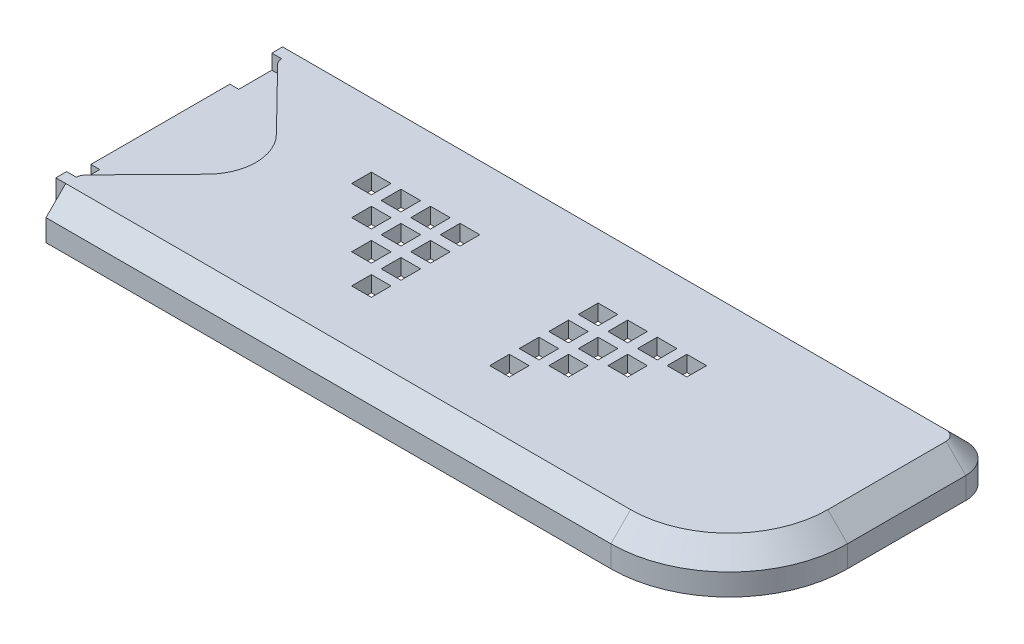
SolidWorks part; units mm, degrees
ref_plane "Спереди" through (0, 0, 0) normal (0, 0, 1) x (1, 0, 0)
ref_plane "Сверху" through (0, 0, 0) normal (0, 1, 0) x (1, 0, 0)
ref_plane "Справа" through (0, 0, 0) normal (1, 0, 0) x (0, 0, -1)
sketch "Эскиз1" plane through (0, 1.5, 0) normal (0, 1, 0) x (1, 0, 0)
  line L1 (46.05, -0.9) -> (-4.2, -0.9) construction
  line L2 (-4.2, -0.9) -> (-4.2, 1.1) construction
  line L3 (-4.2, 1.1) -> (-5.2, 1.1) construction
  line L4 (-5.2, 1.1) -> (-5.2, 4.95) construction
  line L5 (-5.2, 4.95) -> (-7.7, 4.95) construction
  line L6 (-7.7, 4.95) -> (-7.7, 3.95) construction
  line L7 (-7.7, 3.95) -> (-6.8, 3.95) construction
  line L8 (-6.8, 3.95) -> (-6.8, -0.5) construction
  line L9 (-6.8, -0.5) -> (-5.8, -0.5) construction
  line L10 (-5.8, -0.5) -> (-5.8, -2.5) construction
  line L11 (-5.8, -2.5) -> (46.05, -2.5) construction
  line L13 (50.55, -2.5) -> (51.5, -2.5) construction
  line L14 (63.5, 9.5) -> (63.5, 21.5) construction
  line L15 (60.5, 24.5) -> (-5.8, 24.5) construction
  line L16 (-5.8, 24.5) -> (-5.8, 22.5) construction
  line L17 (-5.8, 22.5) -> (-6.8, 22.5) construction
  line L18 (-6.8, 22.5) -> (-6.8, 18.05) construction
  line L19 (-6.8, 18.05) -> (-7.7, 18.05) construction
  line L20 (-7.7, 18.05) -> (-7.7, 17.05) construction
  line L21 (-7.7, 17.05) -> (-5.2, 17.05) construction
  line L22 (-5.2, 17.05) -> (-5.2, 20.9) construction
  line L23 (-5.2, 20.9) -> (-4.2, 20.9) construction
  line L24 (-4.2, 20.9) -> (-4.2, 22.9) construction
  line L25 (-4.2, 22.9) -> (60.5, 22.9) construction
  line L26 (61.9, 21.5) -> (61.9, 9.5) construction
  line L27 (51.5, -0.9) -> (50.55, -0.9) construction
  line L29 (46.05, -0.9) -> (-4.2, -0.9)
  line L30 (-4.2, -0.9) -> (-4.2, 1.1)
  line L31 (-4.2, 1.1) -> (-5.2, 1.1)
  line L32 (-5.2, 1.1) -> (-5.2, 4.95)
  line L33 (-5.2, 4.95) -> (-7.7, 4.95)
  line L34 (-7.7, 4.95) -> (-7.7, 3.95)
  line L35 (-7.7, 3.95) -> (-6.8, 3.95)
  line L36 (-6.8, 3.95) -> (-6.8, -0.5)
  line L37 (-6.8, -0.5) -> (-5.8, -0.5)
  line L38 (-5.8, -0.5) -> (-5.8, -2.5)
  line L39 (-5.8, -2.5) -> (46.05, -2.5)
  line L41 (50.55, -2.5) -> (51.5, -2.5)
  line L42 (63.5, 9.5) -> (63.5, 21.5)
  line L43 (60.5, 24.5) -> (-5.8, 24.5)
  line L44 (-5.8, 24.5) -> (-5.8, 22.5)
  line L45 (-5.8, 22.5) -> (-6.8, 22.5)
  line L46 (-6.8, 22.5) -> (-6.8, 18.05)
  line L47 (-6.8, 18.05) -> (-7.7, 18.05)
  line L48 (-7.7, 18.05) -> (-7.7, 17.05)
  line L49 (-7.7, 17.05) -> (-5.2, 17.05)
  line L50 (-5.2, 17.05) -> (-5.2, 20.9)
  line L51 (-5.2, 20.9) -> (-4.2, 20.9)
  line L52 (-4.2, 20.9) -> (-4.2, 22.9)
  line L53 (-4.2, 22.9) -> (60.5, 22.9)
  line L54 (61.9, 21.5) -> (61.9, 9.5)
  line L55 (51.5, -0.9) -> (50.55, -0.9)
  line L56 (50.55, -0.9) -> (46.05, -0.9)
  line L57 (50.55, -2.5) -> (46.05, -2.5)
  arc A0 (51.5, -2.5) -> (63.5, 9.5) centre (51.5, 9.5) ccw construction
  arc A1 (63.5, 21.5) -> (60.5, 24.5) centre (60.5, 21.5) ccw construction
  arc A2 (61.9, 21.5) -> (60.5, 22.9) centre (60.5, 21.5) ccw construction
  arc A3 (51.5, -0.9) -> (61.9, 9.5) centre (51.5, 9.5) ccw construction
  arc A4 (51.5, -2.5) -> (63.5, 9.5) centre (51.5, 9.5) ccw
  arc A5 (63.5, 21.5) -> (60.5, 24.5) centre (60.5, 21.5) ccw
  arc A6 (61.9, 21.5) -> (60.5, 22.9) centre (60.5, 21.5) ccw
  arc A7 (51.5, -0.9) -> (61.9, 9.5) centre (51.5, 9.5) ccw
extrude "Бобышка-Вытянуть1" add sketch "Эскиз1" along normal blind 4.2
sketch "Эскиз2" plane through (0, 5.7, 0) normal (0, 1, 0) x (1, 0, 0)
  line L0 (-7.7, 17.05) -> (-7.7, 4.95)
  line L24 (-5.8, -2.5) -> (51.5, -2.5)
  line L25 (63.5, 9.5) -> (63.5, 21.5)
  line L26 (60.5, 24.5) -> (-5.8, 24.5)
  line L27 (-5.8, 24.5) -> (-5.8, 22.5)
  line L28 (-5.8, 22.5) -> (-6.8, 22.5)
  line L29 (-6.8, 22.5) -> (-6.8, 18.05)
  line L30 (-6.8, 18.05) -> (-7.7, 18.05)
  line L31 (-7.7, 18.05) -> (-7.7, 17.05)
  line L32 (-7.7, 17.05) -> (-5.2, 17.05)
  line L33 (-5.2, 17.05) -> (-5.2, 20.9)
  line L34 (-5.2, 20.9) -> (-4.2, 20.9)
  line L35 (-4.2, 20.9) -> (-4.2, 22.9)
  line L36 (-4.2, 22.9) -> (60.5, 22.9)
  line L37 (61.9, 21.5) -> (61.9, 9.5)
  line L38 (51.5, -0.9) -> (-4.2, -0.9)
  line L39 (-4.2, -0.9) -> (-4.2, 1.1)
  line L40 (-4.2, 1.1) -> (-5.2, 1.1)
  line L41 (-5.2, 1.1) -> (-5.2, 4.95)
  line L42 (-5.2, 4.95) -> (-7.7, 4.95)
  line L43 (-7.7, 4.95) -> (-7.7, 3.95)
  line L44 (-7.7, 3.95) -> (-6.8, 3.95)
  line L45 (-6.8, 3.95) -> (-6.8, -0.5)
  line L46 (-6.8, -0.5) -> (-5.8, -0.5)
  line L47 (-5.8, -0.5) -> (-5.8, -2.5)
  line L48 (-5.8, -2.5) -> (51.5, -2.5)
  line L49 (63.5, 9.5) -> (63.5, 21.5)
  line L50 (60.5, 24.5) -> (-5.8, 24.5)
  line L51 (-5.8, 24.5) -> (-5.8, 22.5)
  line L52 (-5.8, 22.5) -> (-6.8, 22.5)
  line L53 (-6.8, 22.5) -> (-6.8, 18.05)
  line L54 (-6.8, 18.05) -> (-7.7, 18.05)
  line L55 (-7.7, 18.05) -> (-7.7, 17.05)
  line L67 (-7.7, 4.95) -> (-7.7, 3.95)
  line L68 (-7.7, 3.95) -> (-6.8, 3.95)
  line L69 (-6.8, 3.95) -> (-6.8, -0.5)
  line L70 (-6.8, -0.5) -> (-5.8, -0.5)
  line L71 (-5.8, -0.5) -> (-5.8, -2.5)
  arc A4 (51.5, -2.5) -> (63.5, 9.5) centre (51.5, 9.5) ccw
  arc A5 (63.5, 21.5) -> (60.5, 24.5) centre (60.5, 21.5) ccw
  arc A6 (61.9, 21.5) -> (60.5, 22.9) centre (60.5, 21.5) ccw
  arc A7 (51.5, -0.9) -> (61.9, 9.5) centre (51.5, 9.5) ccw
  arc A8 (51.5, -2.5) -> (63.5, 9.5) centre (51.5, 9.5) ccw
  arc A9 (63.5, 21.5) -> (60.5, 24.5) centre (60.5, 21.5) ccw
  dimension "D1" = 0
extrude "Бобышка-Вытянуть2" add sketch "Эскиз2" against normal blind 1.6
chamfer "Фаска1" distance 2 angle 45 5 edges at (27.35, 5.7, -24.5) (62.6213, 5.7, -23.6213) (63.5, 5.7, -15.5) (59.9853, 5.7, -1.0147) (22.85, 5.7, 2.5)
sketch "Эскиз3" plane through (0, 5.7, 0) normal (0, 1, 0) x (1, 0, 0)
  line L0 (0.5708, 7.5) -> (-5.5142, 1.2916) construction
  line L1 (-5.5142, 20.7084) -> (0.5708, 14.5) construction
  line L2 (0.5708, 7.5) -> (-5.5142, 1.2916)
  line L3 (-5.5142, 20.7084) -> (0.5708, 14.5)
  line L4 (-5.8, 21.4083) -> (-11.5257, 21.4083)
  line L5 (-11.5257, 21.4083) -> (-11.5257, 0.5917)
  line L6 (-11.5257, 0.5917) -> (-5.8, 0.5917)
  arc A0 (-5.5142, 1.2916) -> (-5.8, 0.5917) centre (-4.8, 0.5917) ccw construction
  arc A1 (-5.8, 21.4083) -> (-5.5142, 20.7084) centre (-4.8, 21.4083) ccw construction
  arc A2 (0.5708, 7.5) -> (0.5708, 14.5) centre (-3.0002, 11) ccw construction
  arc A3 (-5.5142, 1.2916) -> (-5.8, 0.5917) centre (-4.8, 0.5917) ccw
  arc A4 (-5.8, 21.4083) -> (-5.5142, 20.7084) centre (-4.8, 21.4083) ccw
  arc A5 (0.5708, 7.5) -> (0.5708, 14.5) centre (-3.0002, 11) ccw
extrude "Вырез-Вытянуть1" cut sketch "Эскиз3" against normal blind 1.5
sketch "Эскиз4" plane through (0, 4.1, 0) normal (0, -1, 0) x (1, 0, 0)
  line L0 (-4.2, 0.9) -> (2.2241, -8.0938)
  line L1 (-4.2, 0.9) -> (-4.2, -1.1) construction
  line L2 (2.2241, -13.9062) -> (-4.2, -22.9)
  line L3 (-4.2, -20.9) -> (-4.2, -22.9) construction
  line L4 (4.3, -11) -> (-7.7, -11) construction
  line L5 (-7.7, -17.05) -> (-7.7, -4.95) construction
  line L6 (-4.2, 0.9) -> (-5.2, -1.1)
  line L7 (-5.2, -1.1) -> (-5.2, -4.95) construction
  line L8 (-4.2, -1.1) -> (-5.2, -1.1) construction
  line L9 (-5.2, -1.1) -> (-5.998, -4.95)
  line L10 (-5.2, -4.95) -> (-7.7, -4.95) construction
  line L11 (-5.998, -4.95) -> (-7.7, -4.95)
  line L12 (-7.7, -4.95) -> (-7.7, -17.05)
  line L13 (-7.7, -17.05) -> (-5.2, -17.05)
  line L14 (-5.2, -17.05) -> (-5.2, -22.9)
  line L15 (-5.2, -22.9) -> (-4.2, -22.9)
  arc A0 (2.2241, -13.9062) -> (2.2241, -8.0938) centre (-1.8445, -11) ccw
  dimension "D2" = 5
  dimension "D1" = 12
extrude "Бобышка-Вытянуть3" add sketch "Эскиз4" along normal blind 1.5
sketch "Эскиз5" plane through (0, 2.6, 0) normal (0, -1, 0) x (1, 0, 0)
  line L1 (-7.7, -4.95) -> (-5.2, -4.95)
  line L2 (-7.7, -4.95) -> (-7.7, -17.05)
  line L3 (-7.7, -17.05) -> (-5.2, -17.05)
  line L4 (-5.2, -4.95) -> (-5.2, -17.05)
extrude "Бобышка-Вытянуть4" add sketch "Эскиз5" along normal up to surface (1.1 mm away) up to face at (12.9125, 1.5, -11.5097)
sketch "Эскиз6" plane through (0, 5.7, 0) normal (0, 1, 0) x (1, 0, 0)
  line L0 (25.7, 22.5) -> (25.7, -0.5) construction
  line L1 (19.7, 16) -> (17.7, 16)
  line L2 (19.7, 16) -> (19.7, 14)
  line L3 (19.7, 14) -> (17.7, 14)
  line L4 (17.7, 16) -> (17.7, 14)
  line L5 (19.7, 16) -> (17.7, 14) construction
  line L6 (19.7, 14) -> (17.7, 16) construction
  line L7 (60.5, 22.5) -> (-5.8, 22.5) construction
  line L8 (-5.8, -0.5) -> (51.5, -0.5) construction
  line L9 (-5.8, 24.5) -> (60.5, 24.5) construction
  line L10 (-6.8, 21.4083) -> (-6.8, 18.05) construction
  line L11 (16.7, 16) -> (14.7, 16)
  line L12 (16.7, 16) -> (16.7, 14)
  line L13 (16.7, 14) -> (14.7, 14)
  line L14 (14.7, 16) -> (14.7, 14)
  line L15 (13.7, 16) -> (11.7, 16)
  line L16 (13.7, 16) -> (13.7, 14)
  line L17 (13.7, 14) -> (11.7, 14)
  line L18 (11.7, 16) -> (11.7, 14)
  line L19 (10.7, 16) -> (8.7, 16)
  line L20 (10.7, 16) -> (10.7, 14)
  line L21 (10.7, 14) -> (8.7, 14)
  line L22 (8.7, 16) -> (8.7, 14)
  line L23 (19.7, 13) -> (17.7, 13)
  line L24 (19.7, 13) -> (19.7, 11)
  line L25 (19.7, 11) -> (17.7, 11)
  line L26 (17.7, 13) -> (17.7, 11)
  line L27 (16.7, 13) -> (14.7, 13)
  line L28 (16.7, 13) -> (16.7, 11)
  line L29 (16.7, 11) -> (14.7, 11)
  line L30 (14.7, 13) -> (14.7, 11)
  line L31 (13.7, 13) -> (11.7, 13)
  line L32 (13.7, 13) -> (13.7, 11)
  line L33 (13.7, 11) -> (11.7, 11)
  line L34 (11.7, 13) -> (11.7, 11)
  line L39 (19.7, 10) -> (17.7, 10)
  line L40 (19.7, 10) -> (19.7, 8)
  line L41 (19.7, 8) -> (17.7, 8)
  line L42 (17.7, 10) -> (17.7, 8)
  line L43 (16.7, 10) -> (14.7, 10)
  line L44 (16.7, 10) -> (16.7, 8)
  line L45 (16.7, 8) -> (14.7, 8)
  line L46 (14.7, 10) -> (14.7, 8)
  line L55 (19.7, 7) -> (17.7, 7)
  line L56 (19.7, 7) -> (19.7, 5)
  line L57 (19.7, 5) -> (17.7, 5)
  line L58 (17.7, 7) -> (17.7, 5)
  line L71 (16.7, 7) -> (14.7, 7) [skipped]
  line L72 (16.7, 7) -> (16.7, 5) [skipped]
  line L73 (16.7, 5) -> (14.7, 5) [skipped]
  line L74 (14.7, 7) -> (14.7, 5) [skipped]
  line L75 (13.7, 7) -> (11.7, 7) [skipped]
  line L76 (13.7, 7) -> (13.7, 5) [skipped]
  line L77 (13.7, 5) -> (11.7, 5) [skipped]
  line L78 (11.7, 7) -> (11.7, 5) [skipped]
  line L79 (10.7, 7) -> (8.7, 7) [skipped]
  line L80 (10.7, 7) -> (10.7, 5) [skipped]
  line L81 (10.7, 5) -> (8.7, 5) [skipped]
  line L82 (8.7, 7) -> (8.7, 5) [skipped]
  line L83 (13.7, 10) -> (11.7, 10) [skipped]
  line L84 (13.7, 10) -> (13.7, 8) [skipped]
  line L85 (13.7, 8) -> (11.7, 8) [skipped]
  line L86 (11.7, 10) -> (11.7, 8) [skipped]
  line L87 (10.7, 10) -> (8.7, 10) [skipped]
  line L88 (10.7, 10) -> (10.7, 8) [skipped]
  line L89 (10.7, 8) -> (8.7, 8) [skipped]
  line L90 (8.7, 10) -> (8.7, 8) [skipped]
  line L91 (10.7, 13) -> (8.7, 13) [skipped]
  line L92 (10.7, 13) -> (10.7, 11) [skipped]
  line L93 (10.7, 11) -> (8.7, 11) [skipped]
  line L94 (8.7, 13) -> (8.7, 11) [skipped]
  line L95 (31.7, 14) -> (33.7, 16) construction
  line L96 (31.7, 16) -> (33.7, 14) construction
  line L97 (33.7, 7) -> (33.7, 5)
  line L98 (31.7, 5) -> (33.7, 5)
  line L99 (31.7, 7) -> (31.7, 5)
  line L100 (31.7, 7) -> (33.7, 7)
  line L101 (36.7, 10) -> (36.7, 8)
  line L102 (34.7, 8) -> (36.7, 8)
  line L103 (34.7, 10) -> (34.7, 8)
  line L104 (34.7, 10) -> (36.7, 10)
  line L105 (33.7, 10) -> (33.7, 8)
  line L106 (31.7, 8) -> (33.7, 8)
  line L107 (31.7, 10) -> (31.7, 8)
  line L108 (31.7, 10) -> (33.7, 10)
  line L109 (39.7, 13) -> (39.7, 11)
  line L110 (37.7, 11) -> (39.7, 11)
  line L111 (37.7, 13) -> (37.7, 11)
  line L112 (37.7, 13) -> (39.7, 13)
  line L113 (36.7, 13) -> (36.7, 11)
  line L114 (34.7, 11) -> (36.7, 11)
  line L115 (34.7, 13) -> (34.7, 11)
  line L116 (34.7, 13) -> (36.7, 13)
  line L117 (33.7, 13) -> (33.7, 11)
  line L118 (31.7, 11) -> (33.7, 11)
  line L119 (31.7, 13) -> (31.7, 11)
  line L120 (31.7, 13) -> (33.7, 13)
  line L121 (42.7, 16) -> (42.7, 14)
  line L122 (40.7, 14) -> (42.7, 14)
  line L123 (40.7, 16) -> (40.7, 14)
  line L124 (40.7, 16) -> (42.7, 16)
  line L125 (39.7, 16) -> (39.7, 14)
  line L126 (37.7, 14) -> (39.7, 14)
  line L127 (37.7, 16) -> (37.7, 14)
  line L128 (37.7, 16) -> (39.7, 16)
  line L129 (36.7, 16) -> (36.7, 14)
  line L130 (34.7, 14) -> (36.7, 14)
  line L131 (34.7, 16) -> (34.7, 14)
  line L132 (34.7, 16) -> (36.7, 16)
  line L133 (33.7, 16) -> (33.7, 14)
  line L134 (31.7, 14) -> (33.7, 14)
  line L135 (31.7, 16) -> (31.7, 14)
  line L136 (31.7, 16) -> (33.7, 16)
  point P0 (18.7, 15)
  point P139 (32.7, 15)
  dimension "D1" = 6
  dimension "D2" = 2
  dimension "D3" = 8.5
  dimension "D4" = 26.5
  dimension "D6" = 11
  dimension "D8" = 11
  dimension "D5" = 4
  dimension "D7" = 4
extrude "Вырез-Вытянуть2" cut sketch "Эскиз6" against normal through all
